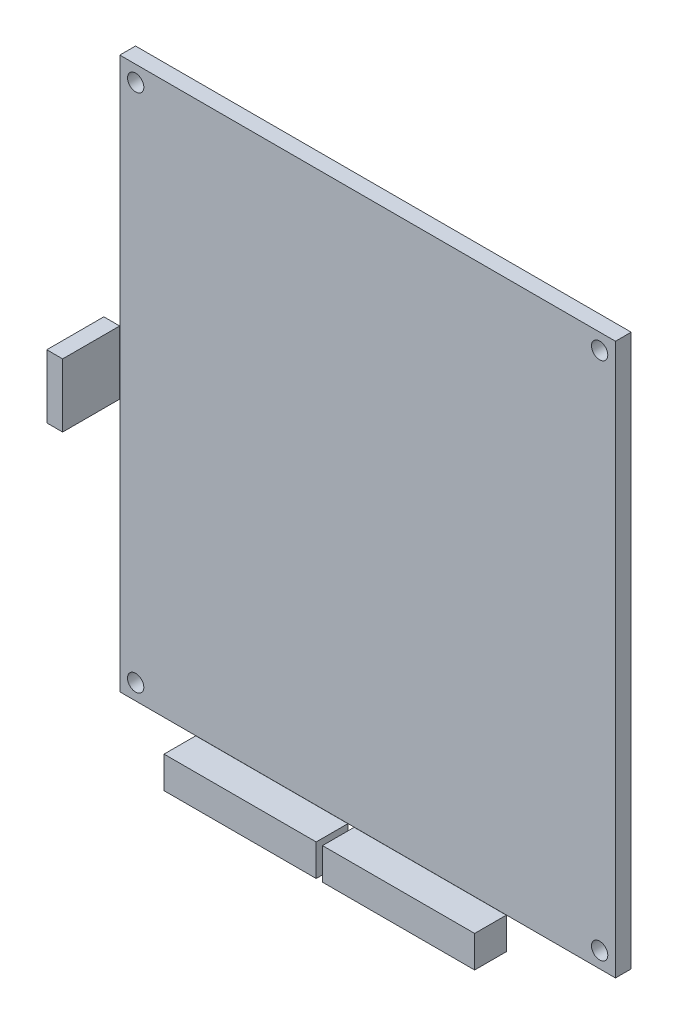
SolidWorks part; units mm, degrees
ref_plane "Front Plane" through (0, 0, 0) normal (0, 0, 1) x (1, 0, 0)
ref_plane "Top Plane" through (0, 0, 0) normal (0, 1, 0) x (1, 0, 0)
ref_plane "Right Plane" through (0, 0, 0) normal (1, 0, 0) x (0, 0, -1)
sketch "Sketch1" plane through (0, 0, 0) normal (0, 0, 1) x (1, 0, 0)
  line L1 (-49.657, -55.245) -> (49.657, -55.245)
  line L2 (-49.657, -55.245) -> (-49.657, 55.245)
  line L3 (-49.657, 55.245) -> (49.657, 55.245)
  line L4 (49.657, -55.245) -> (49.657, 55.245)
  line L5 (-49.657, -55.245) -> (49.657, 55.245) construction
  line L6 (-49.657, 55.245) -> (49.657, -55.245) construction
  point P0 (0, 0)
  dimension "D1" = 99.314
  dimension "D2" = 110.49
extrude "Extrude1" add sketch "Sketch1" along normal blind 3.1496
sketch "Sketch2" plane through (0, -55.245, 0) normal (0, -1, 0) x (1, 0, 0)
  line L0 (-49.657, 3.1496) -> (-49.657, 0) construction
  line L1 (-34.417, 9.525) -> (-3.937, 9.525)
  line L2 (-34.417, 9.525) -> (-34.417, 3.175)
  line L3 (-34.417, 3.175) -> (-3.937, 3.175)
  line L4 (-3.937, 9.525) -> (-3.937, 3.175)
  line L5 (-2.667, 9.525) -> (27.813, 9.525)
  line L6 (-2.667, 9.525) -> (-2.667, 3.175)
  line L7 (-2.667, 3.175) -> (27.813, 3.175)
  line L8 (27.813, 9.525) -> (27.813, 3.175)
  line L9 (-49.657, 0) -> (49.657, 0) construction
  dimension "D1" = 15.24
  dimension "D2" = 46.99
  dimension "D3" = 30.48
  dimension "D4" = 6.35
  dimension "D5" = 3.175
extrude "Extrude2" add sketch "Sketch2" along normal blind 6.35
sketch "Sketch3" plane through (-49.657, 0, 0) normal (-1, 0, 0) x (0, 0, 1)
  line L0 (3.1496, -55.245) -> (0, -55.245) construction
  line L1 (3.175, 8.255) -> (14.605, 8.255)
  line L2 (3.175, 8.255) -> (3.175, -4.445)
  line L3 (3.175, -4.445) -> (14.605, -4.445)
  line L4 (14.605, 8.255) -> (14.605, -4.445)
  line L5 (0, 55.245) -> (0, -55.245) construction
  dimension "D1" = 12.7
  dimension "D2" = 11.43
  dimension "D3" = 50.8
  dimension "D4" = 3.175
extrude "Extrude3" add sketch "Sketch3" along normal blind 3.175
sketch "Sketch4" plane through (0, 0, 3.1496) normal (0, 0, 1) x (1, 0, 0)
  line L0 (-46.482, 55.245) -> (-46.482, 52.07) construction
  line L1 (49.657, 55.245) -> (-49.657, 55.245) construction
  line L2 (-46.482, 52.07) -> (-49.657, 52.07) construction
  line L3 (-49.657, 55.245) -> (-49.657, -55.245) construction
  line L4 (-49.657, -52.07) -> (-46.482, -52.07) construction
  line L5 (-46.482, -52.07) -> (-46.482, -55.245) construction
  line L6 (-49.657, -55.245) -> (49.657, -55.245) construction
  dimension "D1" = 3.175
hole_wizard "#4 Clearance Hole1" positions "3DSketch1" profile "Sketch5" hole size "#4" standard "Ansi Inch" end condition through all
sketch3d "3DSketch1"
  point P0 (-46.482, 52.07, 3.1496)
  point P3 (-46.482, -52.07, 3.1496)
sketch "Sketch5" plane through (-46.482, 52.07, 3.1496) normal (1, 0, 0) x (0, -1, 0)
  line L0 (0, 0) -> (0, 3.1496)
  line L1 (0, 3.1496) -> (1.6319, 3.1496)
  line L2 (1.6319, 3.1496) -> (1.6319, 0)
  line L5 (1.6319, 0) -> (0, 0)
  line L11 (0, -6.35) -> (0, 107.95) construction
  dimension "Thru Hole Dia." = 3.2639
  dimension "Thru Hole Depth" = 3.1496
mirror "Mirror1" about plane through (0, 0, 0) normal (1, 0, 0) of "#4 Clearance Hole1"
